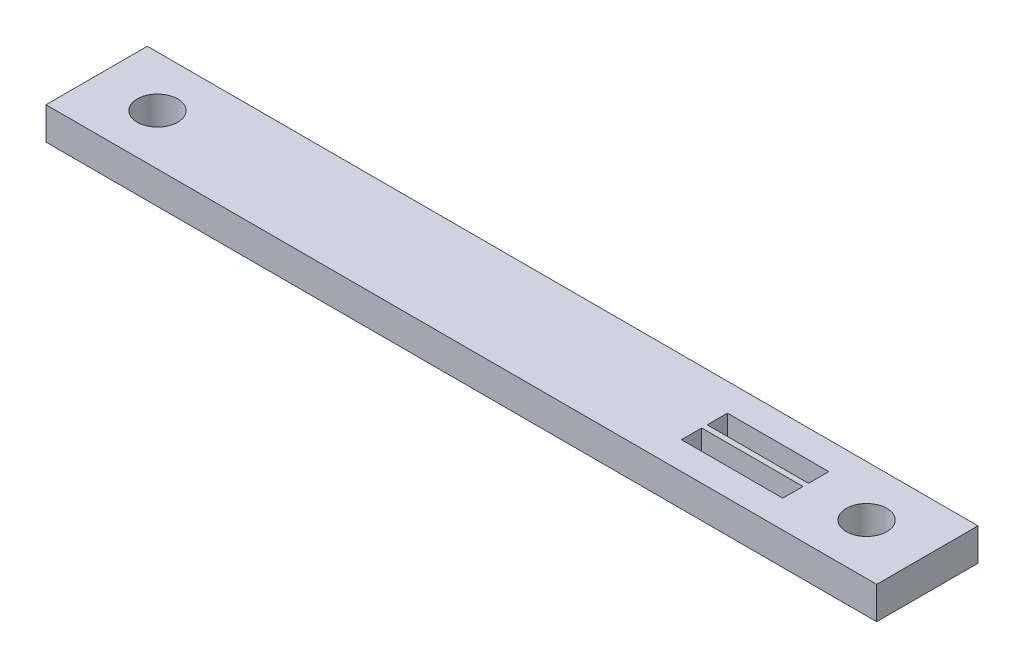
SolidWorks part; units mm, degrees
ref_plane "Front Plane" through (0, 0, 0) normal (0, 0, 1) x (1, 0, 0)
ref_plane "Top Plane" through (0, 0, 0) normal (0, 1, 0) x (1, 0, 0)
ref_plane "Right Plane" through (0, 0, 0) normal (1, 0, 0) x (0, 0, -1)
sketch "Sketch1" plane through (0, 0, 0) normal (0, 1, 0) x (1, 0, 0)
  line L0 (-34, 0) -> (34, 0) construction
  line L1 (-34, -2.5) -> (34, -2.5)
  line L2 (-34, -2.5) -> (-34, 2.5)
  line L3 (-34, 2.5) -> (34, 2.5)
  line L4 (34, -2.5) -> (34, 2.5)
  line L5 (-34, -2.5) -> (34, 2.5) construction
  line L6 (-34, 2.5) -> (34, -2.5) construction
  line L7 (23, 0.635) -> (28, 0.635) construction
  line L8 (23, 1.135) -> (28, 1.135)
  line L9 (23, 1.135) -> (23, 0.135)
  line L10 (23, 0.135) -> (28, 0.135)
  line L11 (28, 1.135) -> (28, 0.135)
  line L12 (23, -0.135) -> (28, -0.135)
  line L13 (23, -0.135) -> (23, -1.135)
  line L14 (23, -1.135) -> (28, -1.135)
  line L15 (28, -0.135) -> (28, -1.135)
  line L16 (23, -0.635) -> (28, -0.635) construction
  line L17 (0, 2.5) -> (0, -2.5) construction
  line L18 (20, 2.5) -> (20, -2.5) construction
  line L19 (31, 2.5) -> (31, -2.5) construction
  line L20 (-1, 2.5) -> (-1, -2.5) construction
  line L21 (-7, 2.5) -> (-7, -2.5)
  line L22 (-7, 0) -> (-1, 0) construction
  circle A0 centre (31, 0) radius 1
  circle A1 centre (0, 0) radius 1 construction
  circle A2 centre (-4, 0) radius 1
  point P0 (0, 0)
  dimension "D2" = 2
  dimension "D10" = 3
  dimension "D12" = 2
  dimension "D13" = 2
  dimension "D1" = 5
  dimension "D3" = 1
  dimension "D4" = 5
  dimension "D5" = 1
  dimension "D6" = 5
  dimension "D7" = 1.27
  dimension "D8" = 20
  dimension "D9" = 3
  dimension "D11" = 6
extrude "Boss-Extrude1" add sketch "Sketch1" along normal blind 1.6 contours L3 L21 L1 L4 A2 A0 L8 L11 L10 L9 L12 L15 L14 L13
